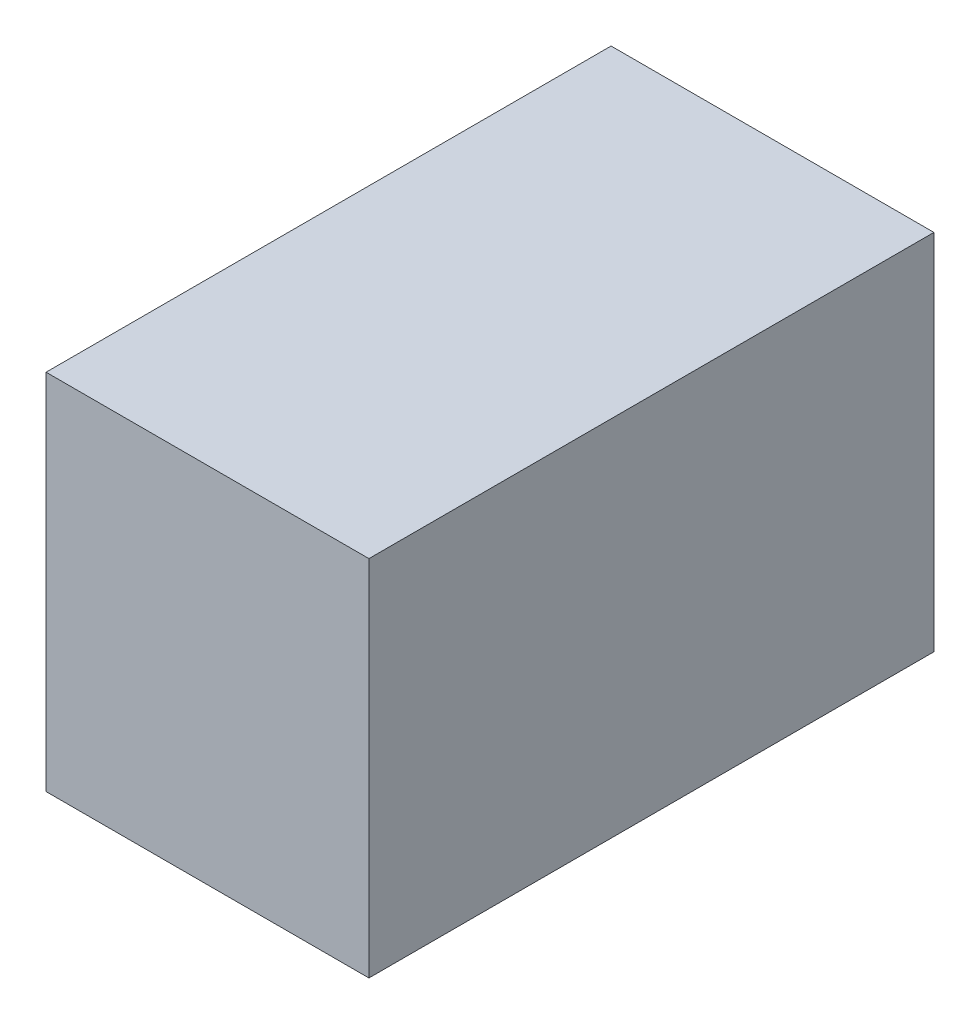
SolidWorks part; units mm, degrees
ref_plane "Front Plane" through (0, 0, 0) normal (0, 0, 1) x (1, 0, 0)
ref_plane "Top Plane" through (0, 0, 0) normal (0, 1, 0) x (1, 0, 0)
ref_plane "Right Plane" through (0, 0, 0) normal (1, 0, 0) x (0, 0, -1)
sketch "Sketch1" plane through (0, 0, 0) normal (0, 1, 0) x (1, 0, 0)
  line L1 (20, -35) -> (-20, -35)
  line L2 (20, -35) -> (20, 35)
  line L3 (20, 35) -> (-20, 35)
  line L4 (-20, -35) -> (-20, 35)
  line L5 (20, -35) -> (-20, 35) construction
  line L6 (20, 35) -> (-20, -35) construction
  point P0 (0, 0)
  dimension "D1" = 70
  dimension "D2" = 40
extrude "Boss-Extrude1" add sketch "Sketch1" along normal blind 45
sketch "Sketch2" plane through (-20, 0, 0) normal (-1, 0, 0) x (0, 0, 1)
  text T0 "Small \r\nTransformer" font "Century Gothic" height in points 20
extrude "Boss-Extrude2" add sketch "Sketch2" along normal blind 1.6
